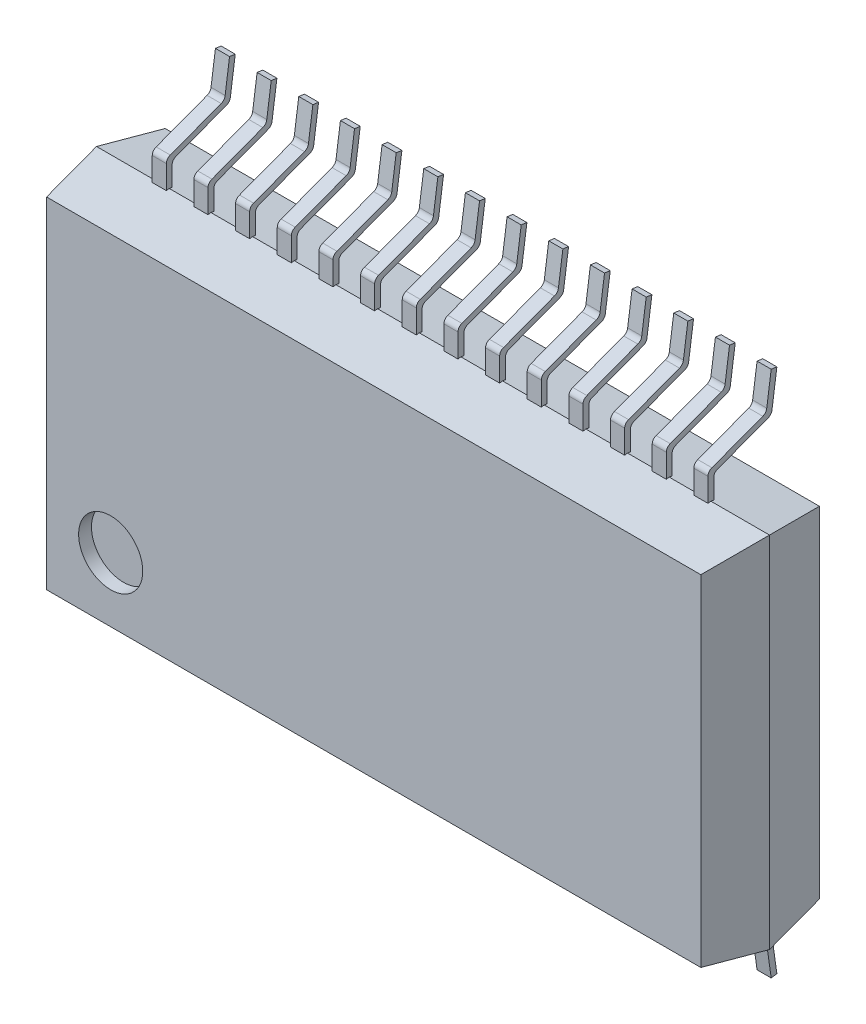
SolidWorks part; units mm, degrees
ref_plane "Plano frontal" through (0, 0, 0) normal (0, 0, 1) x (1, 0, 0)
ref_plane "Plano superior" through (0, 0, 0) normal (0, 1, 0) x (1, 0, 0)
ref_plane "Plano direito" through (0, 0, 0) normal (1, 0, 0) x (0, 0, -1)
sketch "Esboço1" plane through (0, 0, 0) normal (0, 0, 1) x (1, 0, 0)
  line L1 (-0.915, 5.6) -> (9.585, 5.6)
  line L2 (-0.915, 5.6) -> (-0.915, 0)
  line L3 (-0.915, 0) -> (9.585, 0)
  line L4 (9.585, 5.6) -> (9.585, 0)
extrude "Extrusão1" add sketch "Esboço1" along normal blind 0.925 draft 9
sketch "Esboço2" plane through (0, 0, 0) normal (0, 0, 1) x (1, 0, 0)
  line L0 (-0.915, 5.6) -> (9.585, 5.6)
  line L1 (-0.915, 5.6) -> (-0.915, 0)
  line L2 (-0.915, 0) -> (9.585, 0)
  line L3 (9.585, 5.6) -> (9.585, 0)
extrude "Extrusão2" add sketch "Esboço2" against normal blind 0.925 draft 9 separate body
sketch "Esboço3" plane through (0, 0, 0) normal (1, 0, 0) x (0, 0, -1)
  line L2 (1.03, 6.9) -> (0.9409, 6.9125)
  line L4 (-0.045, 5.9583) -> (-0.045, 5.5929)
  line L5 (1.03, 6.9) -> (0.9527, 6.35)
  line L6 (0.0164, 6.0437) -> (0.8104, 6.3425)
  line L7 (0.8719, 6.4214) -> (0.9409, 6.9125)
  line L8 (0.045, 5.896) -> (0.045, 5.5929)
  line L9 (0, 0) -> (0.045, 0.0071)
  line L10 (0.1064, 5.9814) -> (0.8953, 6.2783)
  line L11 (-0.925, 5.4535) -> (0, 5.6) construction
  line L12 (0.925, 5.4535) -> (0, 5.6) construction
  line L13 (-0.045, 5.5929) -> (0, 5.6)
  line L14 (0, 5.6) -> (0.045, 5.5929)
  line L15 (-0.045, 0.0071) -> (0, 0)
  line L16 (0.1064, -0.3814) -> (0.8953, -0.6783)
  line L17 (0.045, -0.296) -> (0.045, 0.0071)
  line L18 (0.8719, -0.8214) -> (0.9409, -1.3125)
  line L19 (0.0164, -0.4437) -> (0.8104, -0.7425)
  line L20 (1.03, -1.3) -> (0.9527, -0.75)
  line L21 (-0.045, -0.3583) -> (-0.045, 0.0071)
  line L22 (1.03, -1.3) -> (0.9409, -1.3125)
  arc A0 (-0.045, 5.9583) -> (0.0164, 6.0437) centre (0.0429, 5.9598) cw
  arc A1 (0.045, 5.896) -> (0.1064, 5.9814) centre (0.1329, 5.8976) cw
  arc A2 (0.8953, 6.2783) -> (0.9527, 6.35) centre (0.8614, 6.3643) ccw
  arc A3 (0.8719, 6.4214) -> (0.8104, 6.3425) centre (0.7796, 6.4299) cw
  arc A4 (0.8719, -0.8214) -> (0.8104, -0.7425) centre (0.7796, -0.8299) ccw
  arc A5 (0.8953, -0.6783) -> (0.9527, -0.75) centre (0.8614, -0.7643) cw
  arc A6 (0.045, -0.296) -> (0.1064, -0.3814) centre (0.1329, -0.2976) ccw
  arc A7 (-0.045, -0.3583) -> (0.0164, -0.4437) centre (0.0429, -0.3598) ccw
extrude "Extrusão3" add sketch "Esboço3" along normal blind 0.22 separate body
pattern_linear "Padrão linear2" count 14 spacing 0.65 along (1, 0, 0) of bodies 104 103
sketch "Esboço7" plane through (0, 0, 0) normal (0, 0, 1) x (1, 0, 0)
  circle A1 centre (0.2315, 1.1465) radius 0.5
extrude "Corte-extrusão1" cut sketch "Esboço7" along normal blind 0.2 and the other way blind 0.2 from surface at 0.925 starting at face at (4.335, 2.8, 0.925)
